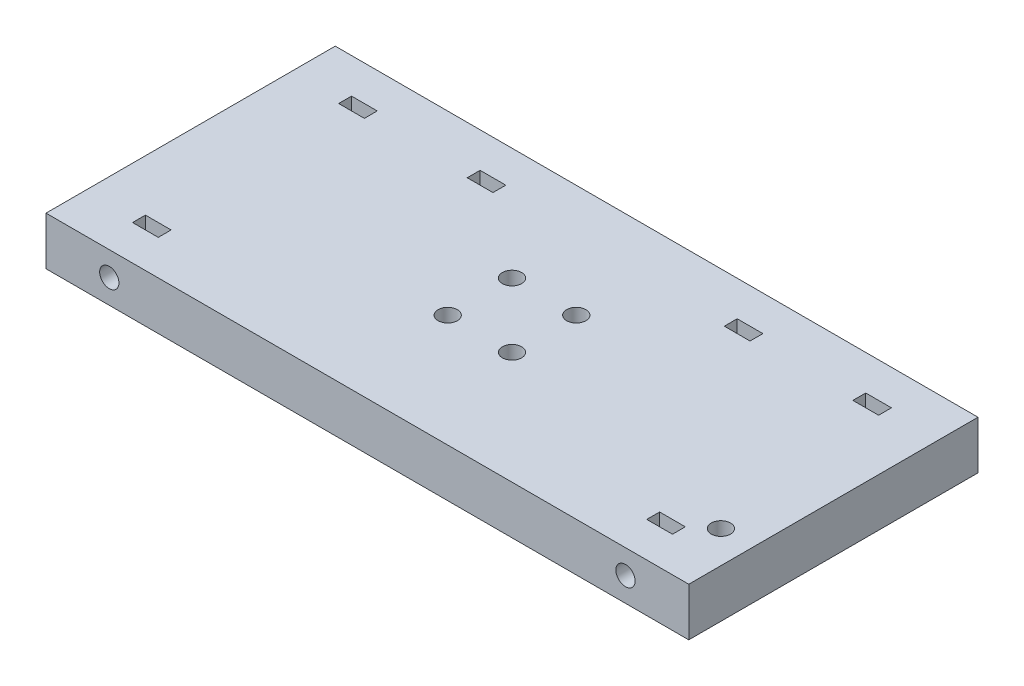
SolidWorks part; units mm, degrees
ref_plane "Front Plane" through (0, 0, 0) normal (0, 0, 1) x (1, 0, 0)
ref_plane "Top Plane" through (0, 0, 0) normal (0, 1, 0) x (1, 0, 0)
ref_plane "Right Plane" through (0, 0, 0) normal (1, 0, 0) x (0, 0, -1)
sketch "Sketch1" plane through (0, 0, 0) normal (0, 1, 0) x (1, 0, 0)
  line L0 (-5.1314, 56.7929) -> (-5.1314, -40.0775) construction
  line L1 (-105.1314, 56.7929) -> (94.8686, 56.7929)
  line L2 (-105.1314, 56.7929) -> (-105.1314, -33.2071)
  line L3 (-105.1314, -33.2071) -> (94.8686, -33.2071)
  line L4 (94.8686, 56.7929) -> (94.8686, -33.2071)
  line L5 (-105.1314, 11.7929) -> (101.6067, 11.7929) construction
  line L6 (-97.6314, 52.8254) -> (-97.6314, 56.7929) construction
  line L7 (-97.6314, 56.7929) -> (-97.6314, -36.8782) construction
  line L8 (-65.1314, 52.8254) -> (-65.1314, 66.5036) construction
  line L9 (-89.1314, 45.8608) -> (-81.1314, 45.8608)
  line L10 (-89.1314, 45.8608) -> (-89.1314, 41.8608)
  line L11 (-89.1314, 41.8608) -> (-81.1314, 41.8608)
  line L12 (-81.1314, 45.8608) -> (-81.1314, 41.8608)
  line L13 (-65.1314, 66.5036) -> (-65.1314, 6.3876) construction
  line L14 (-49.1314, 45.8608) -> (-49.1314, 41.8608)
  line L15 (-41.1314, 45.8608) -> (-49.1314, 45.8608)
  line L16 (-41.1314, 45.8608) -> (-41.1314, 41.8608)
  line L17 (-41.1314, 41.8608) -> (-49.1314, 41.8608)
  line L18 (38.8686, 45.8608) -> (38.8686, 41.8608)
  line L19 (30.8686, 41.8608) -> (38.8686, 41.8608)
  line L20 (30.8686, 45.8608) -> (30.8686, 41.8608)
  line L21 (30.8686, 45.8608) -> (38.8686, 45.8608)
  line L22 (78.8686, 45.8608) -> (70.8686, 45.8608)
  line L23 (70.8686, 45.8608) -> (70.8686, 41.8608)
  line L24 (78.8686, 41.8608) -> (70.8686, 41.8608)
  line L25 (78.8686, 45.8608) -> (78.8686, 41.8608)
  line L26 (70.8686, -22.2751) -> (70.8686, -18.2751)
  line L27 (78.8686, -22.2751) -> (70.8686, -22.2751)
  line L28 (78.8686, -22.2751) -> (78.8686, -18.2751)
  line L29 (78.8686, -18.2751) -> (70.8686, -18.2751)
  line L30 (-81.1314, -22.2751) -> (-81.1314, -18.2751)
  line L31 (-89.1314, -22.2751) -> (-89.1314, -18.2751)
  line L32 (-89.1314, -18.2751) -> (-81.1314, -18.2751)
  line L33 (-89.1314, -22.2751) -> (-81.1314, -22.2751)
  circle A0 centre (-15.1314, 21.7929) radius 3
  circle A1 centre (-15.1314, 1.7929) radius 3
  circle A2 centre (4.8686, 21.7929) radius 3
  circle A3 centre (4.8686, 1.7929) radius 3
  circle A4 centre (84.8686, -13.2071) radius 3
  dimension "D3" = 6
  dimension "D4" = 35
  dimension "D11" = 6
  dimension "D1" = 200
  dimension "D2" = 90
  dimension "D5" = 10
  dimension "D6" = 7.5
  dimension "D7" = 8
  dimension "D8" = 4
  dimension "D9" = 16
  dimension "D10" = 16
  dimension "D12" = 20
  dimension "D13" = 10
extrude "Boss-Extrude1" add sketch "Sketch1" along normal blind 15
sketch "Sketch2" plane through (0, 0, -56.7929) normal (0, 0, -1) x (-1, 0, 0)
  line L0 (-94.8686, 7.5) -> (143.5237, 7.5) construction
  line L1 (-94.8686, 15) -> (-94.8686, 0) construction
  line L2 (5.1314, 15) -> (5.1314, -7.5506) construction
  line L3 (-94.8686, 15) -> (105.1314, 15) construction
  circle A0 centre (-74.8686, 7.5) radius 3
  circle A1 centre (-34.8686, 7.5) radius 3
  circle A2 centre (45.1314, 7.5) radius 3
  circle A3 centre (85.1314, 7.5) radius 3
  dimension "D1" = 6
  dimension "D3" = 6
  dimension "D2" = 20
  dimension "D4" = 40
extrude "Cut-Extrude1" cut sketch "Sketch2" against normal blind 20
sketch "Sketch3" plane through (0, 0, 33.2071) normal (0, 0, 1) x (1, 0, 0)
  line L0 (-105.1314, 7.5) -> (94.8686, 7.5) construction
  line L1 (-105.1314, 15) -> (-105.1314, 0) construction
  line L2 (94.8686, 15) -> (94.8686, 0) construction
  line L3 (-5.1314, 15) -> (-5.1314, -3.8529) construction
  line L4 (-105.1314, 15) -> (94.8686, 15) construction
  circle A0 centre (-85.445, 7.5) radius 3
  circle A1 centre (75.1822, 7.5) radius 3
  dimension "D1" = 6
extrude "Cut-Extrude2" cut sketch "Sketch3" against normal blind 20
